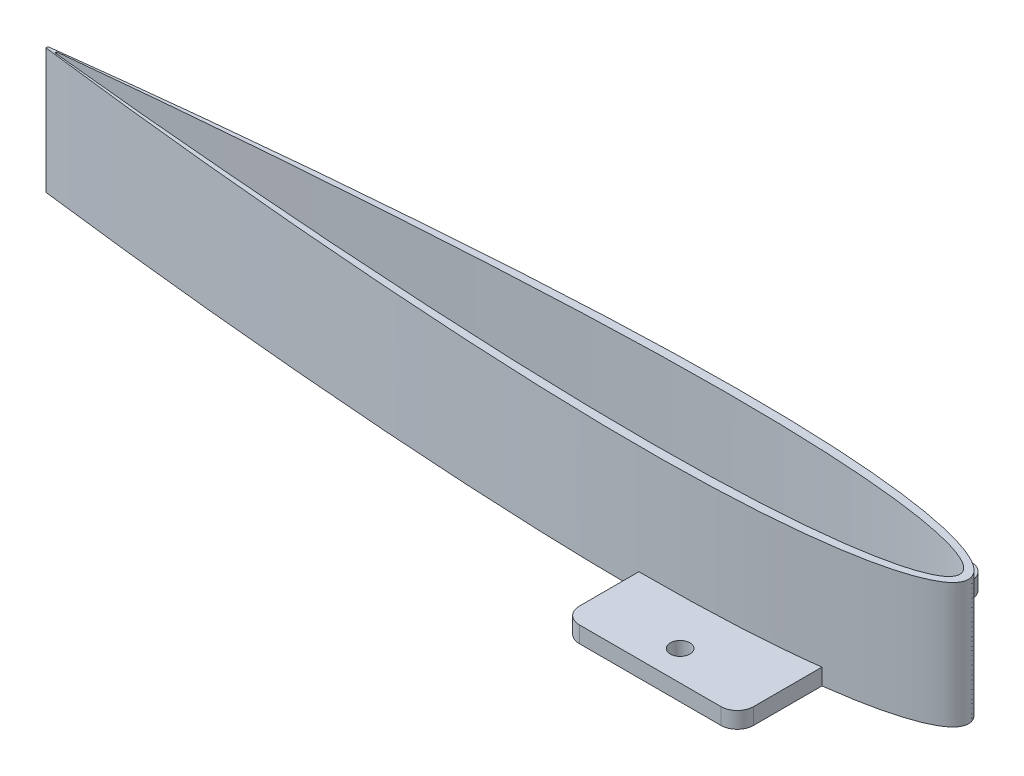
SolidWorks part; units mm, degrees
ref_plane "Front Plane" through (0, 0, 0) normal (0, 0, 1) x (1, 0, 0)
ref_plane "Top Plane" through (0, 0, 0) normal (0, 1, 0) x (1, 0, 0)
ref_plane "Right Plane" through (0, 0, 0) normal (1, 0, 0) x (0, 0, -1)
sketch "Sketch1" plane through (0, 0, 0) normal (0, 1, 0) x (1, 0, 0)
  line L0 (-167.725, 0.1906) -> (-167.725, -0.1906)
  spline S0 degree 3 poles (-167.725, 0.1906) (-167.5704, 0.2099) (-166.9538, 0.2872) (-165.5727, 0.4588) (-163.2877, 0.739) (-160.1237, 1.1195) (-156.1155, 1.5894) (-151.3069, 2.136) (-145.7506, 2.7454) (-139.5075, 3.4028) (-132.6459, 4.0933) (-125.2411, 4.8014) (-117.3742, 5.5111) (-109.1314, 6.206) (-100.6029, 6.8686) (-91.8823, 7.4806) (-83.065, 8.0226) (-74.2476, 8.4749) (-65.5264, 8.8178) (-56.9971, 9.0329) (-48.7528, 9.1042) (-40.8839, 9.0193) (-33.4763, 8.7703) (-26.611, 8.355) (-20.3628, 7.7766) (-14.7994, 7.0443) (-9.9795, 6.1724) (-5.9542, 5.1771) (-2.7529, 4.0819) (-0.4031, 2.8901) (1.1593, 1.6028) (1.7907, 0) (1.1593, -1.6028) (-0.4031, -2.8901) (-2.7529, -4.0819) (-5.9542, -5.1771) (-9.9795, -6.1724) (-14.7994, -7.0443) (-20.3628, -7.7766) (-26.611, -8.355) (-33.4763, -8.7703) (-40.8839, -9.0193) (-48.7528, -9.1042) (-56.9971, -9.0329) (-65.5264, -8.8178) (-74.2476, -8.4749) (-83.065, -8.0226) (-91.8823, -7.4806) (-100.6029, -6.8686) (-109.1314, -6.206) (-117.3742, -5.5111) (-125.2411, -4.8014) (-132.6459, -4.0933) (-139.5075, -3.4028) (-145.7506, -2.7454) (-151.3069, -2.136) (-156.1155, -1.5894) (-160.1237, -1.1195) (-163.2877, -0.739) (-165.5727, -0.4588) (-166.9538, -0.2872) (-167.5704, -0.2099) (-167.725, -0.1906) knots 0 0 0 0 0.001358 0.005418 0.012134 0.02143 0.033203 0.04732 0.063625 0.081937 0.102054 0.123752 0.146792 0.170922 0.195873 0.221373 0.247141 0.272893 0.29835 0.323235 0.34728 0.370229 0.391841 0.411895 0.430187 0.44654 0.460805 0.472869 0.482669 0.490231 0.495773 0.5 0.504227 0.509769 0.517331 0.527131 0.539195 0.55346 0.569813 0.588105 0.608159 0.629771 0.65272 0.676765 0.70165 0.727107 0.752859 0.778627 0.804127 0.829078 0.853208 0.876248 0.897946 0.918063 0.936375 0.95268 0.966797 0.97857 0.987866 0.994582 0.998642 1 1 1 1
extrude "Boss-Extrude1" add sketch "Sketch1" along normal blind 23
sketch "Sketch2" plane through (0, 0, 0) normal (0, 1, 0) x (1, 0, 0)
  line L0 (-46.9, -23) -> (-20.9, -23)
  line L1 (-17.9, -20) -> (-17.9, 20)
  line L2 (-20.9, 23) -> (-46.9, 23)
  line L3 (-49.9, 20) -> (-49.9, -20)
  arc A0 (-20.9, -23) -> (-17.9, -20) centre (-20.9, -20) ccw
  arc A1 (-17.9, 20) -> (-20.9, 23) centre (-20.9, 20) ccw
  arc A2 (-46.9, 23) -> (-49.9, 20) centre (-46.9, 20) ccw
  arc A3 (-49.9, -20) -> (-46.9, -23) centre (-46.9, -20) ccw
extrude "Boss-Extrude2" add sketch "Sketch2" along normal blind 3
ref_plane "Plane1" through (0, 23, 0) normal (0, 1, 0) x (1, 0, 0)
sketch "Sketch3" plane through (0, 23, 0) normal (0, 1, 0) x (1, 0, 0)
  line L0 (-166.125, 0.157) -> (-166.125, -0.157)
  spline S0 degree 3 poles (-166.125, 0.157) (-165.9733, 0.1729) (-165.3683, 0.2365) (-164.0133, 0.3779) (-161.7714, 0.6087) (-158.6672, 0.9221) (-154.7346, 1.3092) (-150.0169, 1.7594) (-144.5655, 2.2614) (-138.4403, 2.803) (-131.7083, 3.3717) (-124.4434, 3.955) (-116.7251, 4.5396) (-108.638, 5.112) (-100.2708, 5.6578) (-91.7149, 6.1619) (-83.0643, 6.6083) (-74.4135, 6.9808) (-65.8573, 7.2633) (-57.4893, 7.4404) (-49.4013, 7.4992) (-41.6816, 7.4292) (-34.4147, 7.2242) (-27.6802, 6.8821) (-21.5514, 6.406) (-16.0952, 5.803) (-11.3692, 5.086) (-7.425, 4.2664) (-4.2915, 3.3722) (-2.0021, 2.3904) (-0.477, 1.376) (0.1972, 0) (-0.477, -1.376) (-2.0021, -2.3904) (-4.2915, -3.3722) (-7.425, -4.2664) (-11.3692, -5.086) (-16.0952, -5.803) (-21.5514, -6.406) (-27.6802, -6.8821) (-34.4147, -7.2242) (-41.6816, -7.4292) (-49.4013, -7.4992) (-57.4893, -7.4404) (-65.8573, -7.2633) (-74.4135, -6.9808) (-83.0643, -6.6083) (-91.7149, -6.1619) (-100.2708, -5.6578) (-108.638, -5.112) (-116.7251, -4.5396) (-124.4434, -3.955) (-131.7083, -3.3717) (-138.4403, -2.803) (-144.5655, -2.2614) (-150.0169, -1.7594) (-154.7346, -1.3092) (-158.6672, -0.9221) (-161.7714, -0.6087) (-164.0133, -0.3779) (-165.3683, -0.2365) (-165.9733, -0.1729) (-166.125, -0.157) knots 0 0 0 0 0.001361 0.005428 0.012156 0.02147 0.033267 0.047415 0.063758 0.082114 0.102282 0.124039 0.147146 0.171348 0.196379 0.221963 0.247821 0.273669 0.299223 0.324206 0.348349 0.37139 0.393087 0.41321 0.431552 0.447929 0.462182 0.474186 0.48386 0.491199 0.496361 0.5 0.503639 0.508801 0.51614 0.525814 0.537818 0.552071 0.568448 0.58679 0.606913 0.62861 0.651651 0.675794 0.700777 0.726331 0.752179 0.778037 0.803621 0.828652 0.852854 0.875961 0.897718 0.917886 0.936242 0.952585 0.966733 0.97853 0.987844 0.994572 0.998639 1 1 1 1
extrude "Cut-Extrude1" cut sketch "Sketch3" against normal blind 20
sketch "Sketch4" plane through (0, 0, 0) normal (0, 1, 0) x (1, 0, 0)
  circle A0 centre (-33.9, -17.5) radius 1.8
  circle A1 centre (-33.9, 17.5) radius 1.8
extrude "Cut-Extrude2" cut sketch "Sketch4" along normal blind 3
